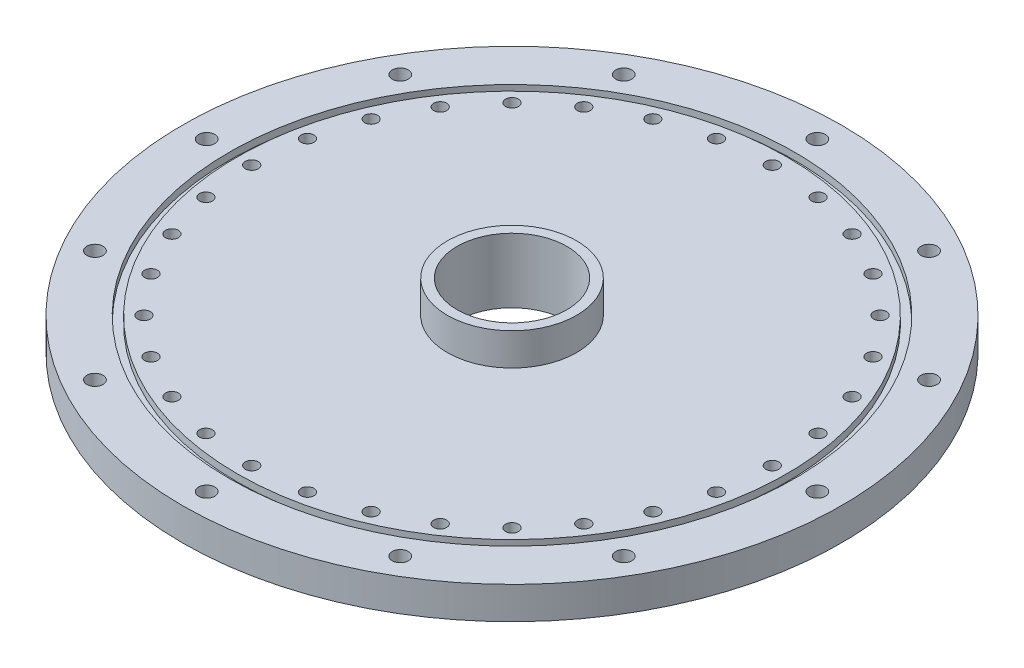
SolidWorks part; units mm, degrees
ref_plane "Front Plane" through (0, 0, 0) normal (0, 0, 1) x (1, 0, 0)
ref_plane "Top Plane" through (0, 0, 0) normal (0, 1, 0) x (1, 0, 0)
ref_plane "Right Plane" through (0, 0, 0) normal (1, 0, 0) x (0, 0, -1)
sketch "Sketch1" plane through (0, 0, 0) normal (0, 1, 0) x (1, 0, 0)
  circle A0 centre (0, 0) radius 129.54
  circle A1 centre (0, 0) radius 21.59
  circle A2 centre (0, 120.015) radius 3.175
  circle A3 centre (60.0075, 103.936) radius 3.175
  circle A4 centre (103.936, 60.0075) radius 3.175
  circle A5 centre (120.015, 0) radius 3.175
  circle A6 centre (103.936, -60.0075) radius 3.175
  circle A7 centre (60.0075, -103.936) radius 3.175
  circle A8 centre (0, -120.015) radius 3.175
  circle A9 centre (-60.0075, -103.936) radius 3.175
  circle A10 centre (-103.936, -60.0075) radius 3.175
  circle A11 centre (-120.015, 0) radius 3.175
  circle A12 centre (-103.936, 60.0075) radius 3.175
  circle A13 centre (-60.0075, 103.936) radius 3.175
  point P4 (0, 120.015)
  point P31 (0, 0)
  dimension "D1" = 259.08
  dimension "D2" = 43.18
  dimension "D4" = 6.35
  dimension "D3" = 120.015
  dimension "D5" = 12
extrude "Boss-Extrude1" add sketch "Sketch1" along normal blind 12.7
sketch "Sketch2" plane through (0, 12.7, 0) normal (0, 1, 0) x (1, 0, 0)
  circle A0 centre (0, 0) radius 111.125
  circle A1 centre (0, 0) radius 107.95
  dimension "D1" = 222.25
  dimension "D2" = 215.9
extrude "Cut-Extrude1" cut sketch "Sketch2" against normal blind 2.794
sketch "Sketch3" plane through (0, 12.7, 0) normal (0, 1, 0) x (1, 0, 0)
  point P0 (0, 102.3112)
  point P5 (19.9599, 100.3453)
  point P6 (39.1528, 94.5232)
  point P7 (56.8411, 85.0687)
  point P8 (72.3449, 72.3449)
  point P9 (85.0687, 56.8411)
  point P10 (94.5232, 39.1528)
  point P11 (100.3453, 19.9599)
  point P12 (102.3112, 0)
  point P13 (100.3453, -19.9599)
  point P14 (94.5232, -39.1528)
  point P15 (85.0687, -56.8411)
  point P16 (72.3449, -72.3449)
  point P17 (56.8411, -85.0687)
  point P18 (39.1528, -94.5232)
  point P19 (19.9599, -100.3453)
  point P20 (0, -102.3112)
  point P21 (-19.9599, -100.3453)
  point P22 (-39.1528, -94.5232)
  point P23 (-56.8411, -85.0687)
  point P24 (-72.3449, -72.3449)
  point P25 (-85.0687, -56.8411)
  point P26 (-94.5232, -39.1528)
  point P27 (-100.3453, -19.9599)
  point P28 (-102.3112, 0)
  point P29 (-100.3453, 19.9599)
  point P30 (-94.5232, 39.1528)
  point P31 (-85.0687, 56.8411)
  point P32 (-72.3449, 72.3449)
  point P33 (-56.8411, 85.0687)
  point P34 (-39.1528, 94.5232)
  point P35 (-19.9599, 100.3453)
  point P36 (0, 0)
  dimension "D1" = 102.3112
  dimension "D2" = 32
hole_wizard "1/4 (0.2) Diameter Hole1" positions "3DSketch1" profile "Sketch4" hole size "1/4" standard "ANSI Inch" end condition through all
sketch3d "3DSketch1"
  point P0 (19.9599, 12.7, -100.3453)
  point P3 (39.1528, 12.7, -94.5232)
  point P6 (56.8411, 12.7, -85.0687)
  point P9 (72.3449, 12.7, -72.3449)
  point P12 (85.0687, 12.7, -56.8411)
  point P15 (94.5232, 12.7, -39.1528)
  point P18 (100.3453, 12.7, -19.9599)
  point P21 (102.3112, 12.7, 0)
  point P24 (100.3453, 12.7, 19.9599)
  point P27 (94.5232, 12.7, 39.1528)
  point P30 (85.0687, 12.7, 56.8411)
  point P33 (72.3449, 12.7, 72.3449)
  point P36 (56.8411, 12.7, 85.0687)
  point P39 (39.1528, 12.7, 94.5232)
  point P42 (19.9599, 12.7, 100.3453)
  point P45 (0, 12.7, 102.3112)
  point P48 (-19.9599, 12.7, 100.3453)
  point P51 (-39.1528, 12.7, 94.5232)
  point P54 (-56.8411, 12.7, 85.0687)
  point P57 (-72.3449, 12.7, 72.3449)
  point P60 (-85.0687, 12.7, 56.8411)
  point P63 (-94.5232, 12.7, 39.1528)
  point P66 (-100.3453, 12.7, 19.9599)
  point P69 (-102.3112, 12.7, 0)
  point P72 (-100.3453, 12.7, -19.9599)
  point P75 (-94.5232, 12.7, -39.1528)
  point P78 (-85.0687, 12.7, -56.8411)
  point P81 (-72.3449, 12.7, -72.3449)
  point P84 (-56.8411, 12.7, -85.0687)
  point P87 (-39.1528, 12.7, -94.5232)
  point P90 (-19.9599, 12.7, -100.3453)
  point P93 (0, 12.7, -102.3112)
sketch "Sketch4" plane through (19.9599, 12.7, -100.3453) normal (1, 0, 0) x (0, 0, 1)
  line L0 (0, 0) -> (0, 12.7)
  line L1 (0, 12.7) -> (2.54, 12.7)
  line L2 (2.54, 12.7) -> (2.54, 0)
  line L5 (2.54, 0) -> (0, 0)
  line L11 (0, -6.35) -> (0, 107.95) construction
  dimension "Thru Hole Dia." = 5.08
  dimension "Thru Hole Depth" = 12.7
sketch "Sketch5" plane through (0, 12.7, 0) normal (0, 1, 0) x (1, 0, 0)
  circle A0 centre (0, 0) radius 21.59
  circle A1 centre (0, 0) radius 25.4
  dimension "D1" = 43.18
  dimension "D2" = 50.8
extrude "Boss-Extrude2" add sketch "Sketch5" along normal blind 12.7
